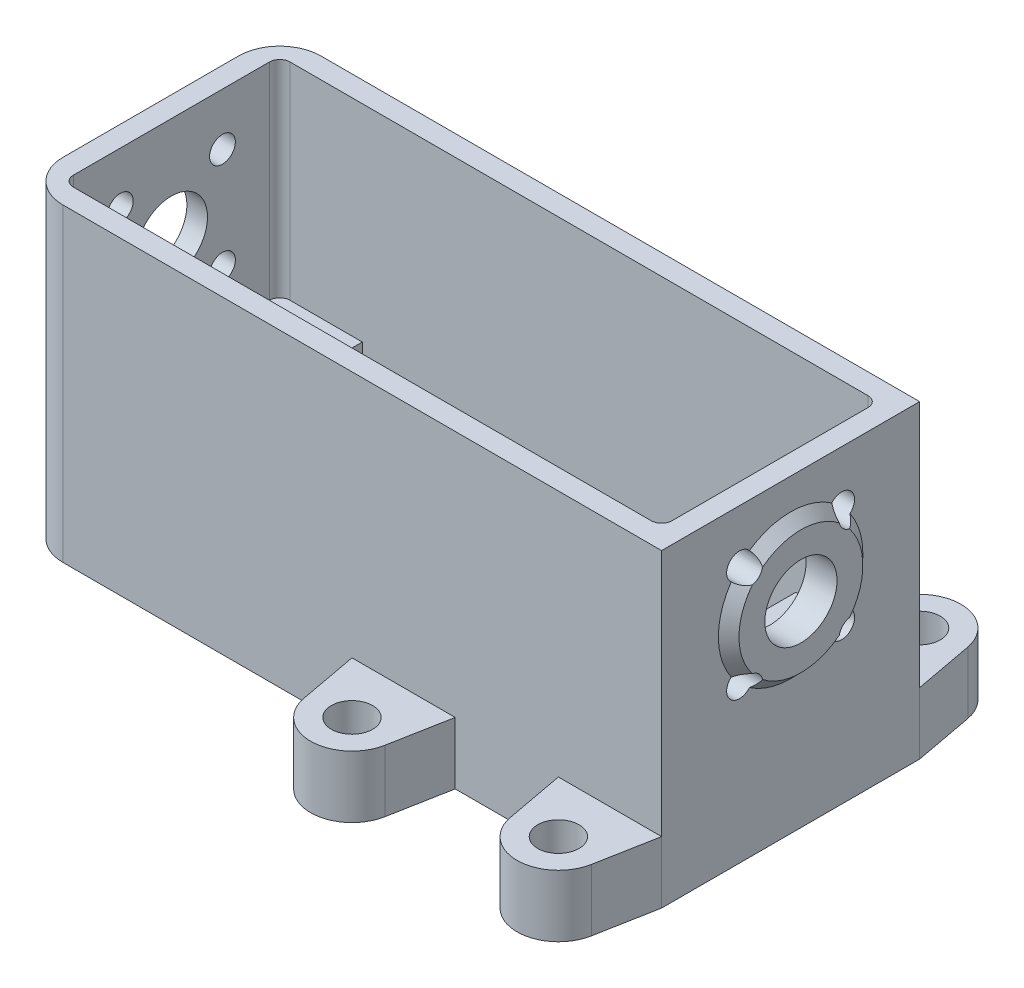
SolidWorks part; units mm, degrees
ref_plane "前视基准面" through (0, 0, 0) normal (0, 0, 1) x (1, 0, 0)
ref_plane "上视基准面" through (0, 0, 0) normal (0, 1, 0) x (1, 0, 0)
ref_plane "右视基准面" through (0, 0, 0) normal (1, 0, 0) x (0, 0, -1)
sketch "草图1" plane through (0, 0, 0) normal (0, 1, 0) x (1, 0, 0)
  line L1 (-31, -12.5) -> (31, -12.5)
  line L2 (-31, -12.5) -> (-31, 12.5)
  line L3 (-31, 12.5) -> (31, 12.5)
  line L4 (31, -12.5) -> (31, 12.5)
  line L5 (-31, -12.5) -> (31, 12.5) construction
  line L6 (-31, 12.5) -> (31, -12.5) construction
  point P0 (0, 0)
  dimension "D1" = 62
  dimension "D2" = 25
extrude "凸台-拉伸1" add sketch "草图1" along normal blind 30
shell "抽壳1" thickness 2
sketch "草图2" plane through (0, 2, 0) normal (0, 1, 0) x (1, 0, 0)
  line L0 (-29, -10.5) -> (29, -10.5) construction
  line L1 (-29, 10.5) -> (-21, 10.5)
  line L2 (-29, 10.5) -> (-29, -10.5)
  line L3 (-29, -10.5) -> (-21, -10.5)
  line L4 (-21, 10.5) -> (-21, -10.5)
  line L5 (29, 10.5) -> (-29, 10.5) construction
  line L6 (21, 10.5) -> (29, 10.5)
  line L7 (21, 10.5) -> (21, -10.5)
  line L8 (21, -10.5) -> (29, -10.5)
  line L9 (29, 10.5) -> (29, -10.5)
  line L10 (29, -10.5) -> (29, 10.5) construction
  line L11 (29, -10.5) -> (29, 10.5) construction
  dimension "D1" = 8
  dimension "D2" = 8
extrude "凸台-拉伸2" add sketch "草图2" along normal blind 8
sketch "草图3" plane through (0, 10, 0) normal (0, 1, 0) x (1, 0, 0)
  line L0 (0, 0) -> (0, 16.0703) construction
  line L1 (29, -10.5) -> (29, 10.5) construction
  line L2 (29, 10.5) -> (21, 10.5) construction
  circle A0 centre (25, -5) radius 2
  circle A1 centre (25, 5) radius 2
  circle A2 centre (-25, 5) radius 2
  circle A3 centre (-25, -5) radius 2
  dimension "D1" = 4
  dimension "D2" = 4
  dimension "D3" = 5.5
  dimension "D4" = 10
extrude "切除-拉伸1" cut sketch "草图3" against normal through all
sketch "草图4" plane through (0, 2, 0) normal (0, 1, 0) x (1, 0, 0)
  line L0 (-21, -10.5) -> (-21, 10.5) construction
  circle A0 centre (-12, 0) radius 6
  dimension "D2" = 12
  dimension "D1" = 9
extrude "切除-拉伸2" cut sketch "草图4" against normal through all
sketch "草图5" plane through (0, 0, 0) normal (0, 1, 0) x (1, 0, 0)
  line L0 (22.0676, 18.2324) -> (21, 12.5)
  line L1 (31, 12.5) -> (-31, 12.5) construction
  line L2 (21, 12.5) -> (31, 12.5)
  line L3 (31, 12.5) -> (29.9324, 18.2324)
  line L4 (26, 17.5) -> (26, 12.5) construction
  line L5 (2.0676, 18.2324) -> (1, 12.5)
  line L6 (11, 12.5) -> (9.9324, 18.2324)
  line L7 (0, 0) -> (31, 0) construction
  line L8 (31, -12.5) -> (31, 12.5) construction
  line L9 (26, -17.5) -> (26, -12.5) construction
  line L10 (11, -12.5) -> (9.9324, -18.2324)
  line L11 (2.0676, -18.2324) -> (1, -12.5)
  line L12 (31, -12.5) -> (29.9324, -18.2324)
  line L13 (21, -12.5) -> (31, -12.5)
  line L14 (22.0676, -18.2324) -> (21, -12.5)
  line L15 (11, 12.5) -> (1, 12.5)
  line L16 (1, -12.5) -> (11, -12.5)
  arc A0 (29.9324, 18.2324) -> (22.0676, 18.2324) centre (26, 17.5) ccw
  circle A1 centre (26, 17.5) radius 2
  circle A2 centre (6, 17.5) radius 2
  arc A3 (9.9324, 18.2324) -> (2.0676, 18.2324) centre (6, 17.5) ccw
  arc A4 (9.9324, -18.2324) -> (2.0676, -18.2324) centre (6, -17.5) cw
  circle A5 centre (6, -17.5) radius 2
  circle A6 centre (26, -17.5) radius 2
  arc A7 (29.9324, -18.2324) -> (22.0676, -18.2324) centre (26, -17.5) cw
  dimension "D2" = 4
  dimension "D3" = 4
  dimension "D4" = 5
  dimension "D1" = 5
  dimension "D6" = 20
  dimension "D5" = 2
extrude "凸台-拉伸3" add sketch "草图5" along normal blind 6
sketch "草图6" plane through (31, 0, 0) normal (1, 0, 0) x (0, 0, -1)
  circle A0 centre (0, 20) radius 7
  dimension "D1" = 20
  dimension "D2" = 14
extrude "凸台-拉伸4" add sketch "草图6" along normal blind 1
sketch "草图7" plane through (0, 0, 0) normal (0, 0, 1) x (1, 0, 0)
  line L0 (31, 27) -> (33, 27)
  line L1 (33, 27) -> (33, 25)
  line L2 (33, 25) -> (31, 27)
  line L3 (31, 30) -> (31, 6) construction
  dimension "D1" = 45
  dimension "D2" = 2
revolve "切除-旋转1" cut sketch "草图7" angle 360 about axis through (32, 20, 0) along (-1, 0, 0)
sketch "草图10" plane through (-31, 0, 0) normal (-1, 0, 0) x (0, 0, 1)
  line L0 (0, 20) -> (0, 30) construction
  line L1 (-12.5, 30) -> (12.5, 30) construction
  line L2 (0, 20) -> (-4.9497, 24.9497) construction
  circle A0 centre (0, 20) radius 3.5
  circle A1 centre (-4.9497, 24.9497) radius 1.25
  circle A2 centre (4.9497, 24.9497) radius 1.25
  circle A3 centre (4.9497, 15.0503) radius 1.25
  circle A4 centre (-4.9497, 15.0503) radius 1.25
  point P17 (0, 20)
  dimension "D1" = 7
  dimension "D4" = 2.5
  dimension "D5" = 20
  dimension "D2" = 45
  dimension "D3" = 7
  dimension "D6" = 4
extrude "切除-拉伸3" cut sketch "草图10" against normal through all
fillet "圆角1" radius 4 2 edges at (-31, 15, -12.5) (-31, 15, 12.5)
fillet "圆角2" radius 1 4 edges at (29, 20, -10.5) (-29, 20, 10.5) (29, 20, 10.5) (-29, 20, -10.5)
move or copy body "实体-移动/复制1" [suppressed] bodies to move or copy 113
move or copy body "实体-移动/复制2" [suppressed] bodies to move or copy 114 parameters "D1"=0, "D2"=0, "D3"=0
move or copy body "实体-移动/复制3" [suppressed] bodies to move or copy 115 parameters "D1"=0, "D2"=0, "D3"=0
